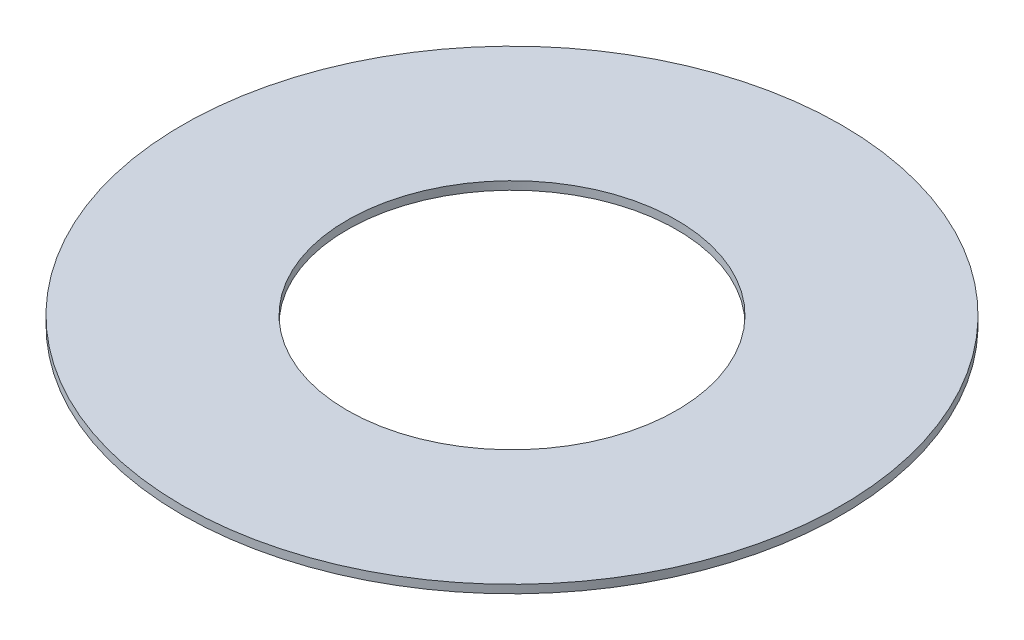
SolidWorks part; units mm, degrees
material "Stainless Steel (ferritic)"
ref_plane "Front Plane" through (0, 0, 0) normal (0, 0, 1) x (1, 0, 0)
ref_plane "Top Plane" through (0, 0, 0) normal (0, 1, 0) x (1, 0, 0)
ref_plane "Right Plane" through (0, 0, 0) normal (1, 0, 0) x (0, 0, -1)
sketch "Sketch1" plane through (0, 0, 0) normal (0, 1, 0) x (1, 0, 0)
  line L0 (-4, 0) -> (4, 0) construction
  circle A0 centre (0, 0) radius 4 construction
  circle A1 centre (0, 0) radius 2 construction
  point P6 (-2, 0)
  point P7 (2, 0)
  point P8 (0, -4)
  point P9 (0, 4)
  dimension "OD" = 8
  dimension "ID" = 4
sketch "Sketch2" plane through (0, 0, 0) normal (1, 0, 0) x (0, 0, -1)
  line L1 (-4, 0.05) -> (4, 0.05) construction
  line L2 (-4, 0.05) -> (-4, -0.05) construction
  line L3 (-4, -0.05) -> (4, -0.05) construction
  line L4 (4, 0.05) -> (4, -0.05) construction
  dimension "Thickness" = 0.1
sketch "Sketch3" plane through (0, 0, 0) normal (0, 1, 0) x (1, 0, 0)
  circle A0 centre (0, 0) radius 4
  circle A1 centre (0, 0) radius 2
extrude "Boss-Extrude1" add sketch "Sketch3" along normal up to vertex (0.05 mm away) and the other way up to vertex (0.05 mm away) up to point (0, 0.05, -4) other way up to point (0, -0.05, -4)
